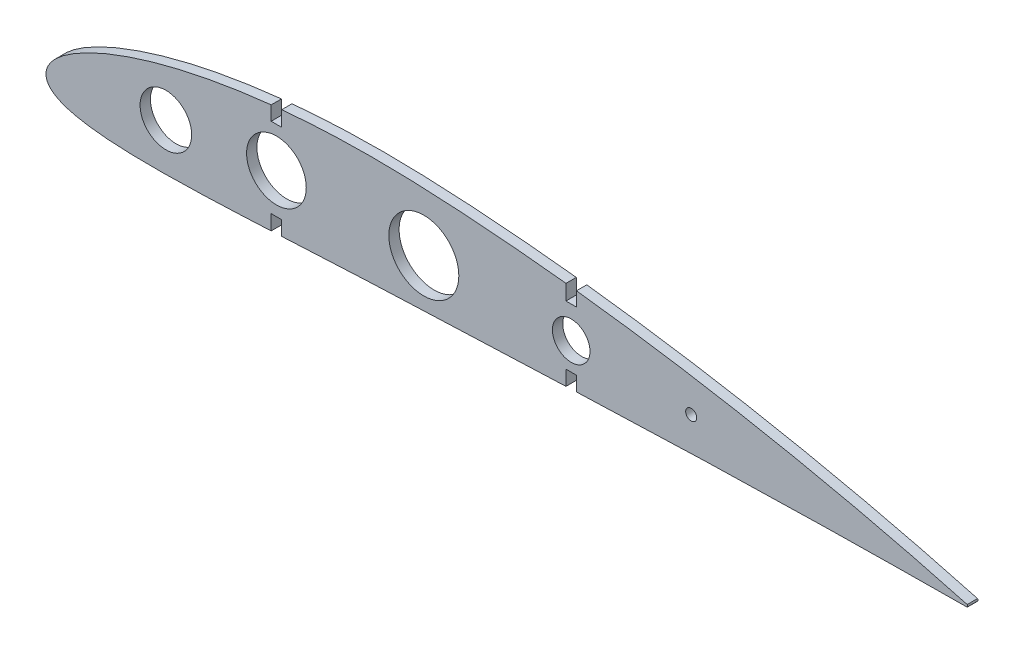
SolidWorks part; units mm, degrees
material "Фанера"
ref_plane "Front Plane" through (0, 0, 0) normal (0, 0, 1) x (1, 0, 0)
ref_plane "Top Plane" through (0, 0, 0) normal (0, 1, 0) x (1, 0, 0)
ref_plane "Right Plane" through (0, 0, 0) normal (1, 0, 0) x (0, 0, -1)
curve "Кривая5"
  spline degree 3 poles (0.048, 0.6214, 0) (0.0227, 0.3735, 0) (-0.0278, -0.1225, 0) (0.078, -0.8844, 0) (0.3497, -1.6388, 0) (0.8143, -2.3651, 0) (1.4635, -3.0393, 0) (2.291, -3.661, 0) (3.3059, -4.2358, 0) (4.5353, -4.7737, 0) (6.0297, -5.2822, 0) (7.869, -5.7653, 0) (10.1688, -6.2217, 0) (13.0754, -6.6396, 0) (16.7281, -6.993, 0) (21.19, -7.2473, 0) (26.4, -7.3766, 0) (32.1974, -7.3763, 0) (38.3978, -7.2614, 0) (44.8576, -7.0566, 0) (51.4865, -6.7865, 0) (58.231, -6.4723, 0) (65.0521, -6.1329, 0) (71.9108, -5.784, 0) (78.7714, -5.4397, 0) (85.6105, -5.111, 0) (92.4321, -4.805, 0) (99.255, -4.532, 0) (106.0974, -4.2783, 0) (112.9692, -4.0031, 0) (119.8644, -3.7232, 0) (126.7739, -3.4401, 0) (133.6816, -3.1587, 0) (140.5819, -2.8824, 0) (147.472, -2.6139, 0) (154.3526, -2.3556, 0) (161.225, -2.1094, 0) (168.0909, -1.8766, 0) (174.9516, -1.6586, 0) (181.8086, -1.4564, 0) (188.6632, -1.2704, 0) (195.5166, -1.1011, 0) (202.3695, -0.9486, 0) (209.2212, -0.8129, 0) (216.0668, -0.6936, 0) (222.8864, -0.5903, 0) (229.6176, -0.5029, 0) (236.0874, -0.4315, 0) (241.9808, -0.3765, 0) (246.559, -0.3395, 0) (249.1205, -0.3213, 0) (250, -0.315, 0) knots 0 0 0 0 0.002941 0.005884 0.009016 0.012365 0.016008 0.020037 0.024574 0.029784 0.035897 0.04324 0.052276 0.063635 0.077983 0.095698 0.11652 0.139661 0.164312 0.189919 0.216157 0.242838 0.269834 0.296993 0.324123 0.351139 0.378036 0.404946 0.431961 0.459078 0.486347 0.513641 0.540929 0.568176 0.59538 0.622543 0.649673 0.676775 0.703855 0.730919 0.757971 0.785018 0.812062 0.839103 0.866132 0.893099 0.919831 0.94581 0.969681 0.98959 1 1 1 1
curve "Кривая6"
  spline degree 3 poles (250, 0.315, 0) (249.1557, 0.545, 0) (246.7202, 1.2085, 0) (242.3913, 2.3583, 0) (236.8498, 3.7876, 0) (230.7799, 5.298, 0) (224.4559, 6.8129, 0) (218.0305, 8.2916, 0) (211.5624, 9.7197, 0) (205.0724, 11.0924, 0) (198.568, 12.4079, 0) (192.0524, 13.6653, 0) (185.5276, 14.8641, 0) (178.9953, 16.0034, 0) (172.4571, 17.0824, 0) (165.9143, 18.0998, 0) (159.3687, 19.0545, 0) (152.8218, 19.9449, 0) (146.2754, 20.7693, 0) (139.7314, 21.5257, 0) (133.1918, 22.212, 0) (126.6587, 22.8257, 0) (120.1368, 23.364, 0) (113.6286, 23.8247, 0) (107.1527, 24.2002, 0) (100.7411, 24.4984, 0) (94.4118, 24.6866, 0) (88.1559, 24.7401, 0) (81.949, 24.6588, 0) (75.7805, 24.441, 0) (69.6537, 24.0819, 0) (63.5754, 23.578, 0) (57.5552, 22.9249, 0) (51.6058, 22.1191, 0) (45.7444, 21.1566, 0) (39.9959, 20.0354, 0) (34.3979, 18.7563, 0) (29.0104, 17.3276, 0) (23.9258, 15.7719, 0) (19.2707, 14.1343, 0) (15.1791, 12.4833, 0) (11.7405, 10.8956, 0) (8.9594, 9.4296, 0) (6.7609, 8.1086, 0) (5.0337, 6.9246, 0) (3.6717, 5.8542, 0) (2.5921, 4.8713, 0) (1.7382, 3.9526, 0) (1.0699, 3.0809, 0) (0.5716, 2.2416, 0) (0.2158, 1.4308, 0) (0.1023, 0.8832, 0) (0.048, 0.6214, 0) knots 0 0 0 0 0.010162 0.029313 0.052012 0.076619 0.101948 0.127526 0.153184 0.178868 0.204558 0.230246 0.255926 0.281594 0.307246 0.332878 0.358485 0.384061 0.409603 0.435104 0.460559 0.485959 0.511303 0.536552 0.561723 0.586629 0.611085 0.635251 0.659272 0.683164 0.706922 0.730536 0.753983 0.777235 0.800246 0.822951 0.845237 0.866916 0.887662 0.906968 0.924203 0.938879 0.950932 0.960693 0.968647 0.975233 0.980795 0.985584 0.989782 0.993521 0.996902 1 1 1 1
sketch "Эскиз1" plane through (0, 0, 0) normal (0, 0, 1) x (1, 0, 0)
  line L0 (250.1305, 0) -> (250.1305, 54.8427) construction
  line L1 (0, 0) -> (0, 70.5199) construction
  line L2 (0, 0) -> (253.0634, 0) construction
  line L3 (62.5326, 62.6361) -> (62.5326, -41.5636) construction
  line L4 (142.5326, 67.9319) -> (142.5326, 25.1988) construction
  line L5 (175.0913, 63.8571) -> (175.0913, -32.3947) construction
  line L6 (32.5326, -14.3434) -> (32.5326, 29.5903) construction
  line L7 (142.5326, 21.1988) -> (142.5326, -57.0034) construction
  line L8 (61.1076, 19.4501) -> (63.9576, 19.4501)
  line L9 (61.1076, 19.4501) -> (61.1076, 23.3031)
  line L11 (63.9576, 19.4501) -> (63.9576, 23.5885)
  line L12 (61.1076, 19.4501) -> (62.5326, 23.4501) construction
  line L13 (62.5326, 23.4501) -> (63.9576, 19.4501) construction
  line L15 (61.1076, -6.3284) -> (61.1076, -2.2577)
  line L16 (61.1076, -2.2577) -> (63.9576, -2.2577)
  line L17 (63.9576, -6.1866) -> (63.9576, -2.2577)
  line L18 (62.5326, -6.2577) -> (63.9576, -2.2577) construction
  line L19 (61.1076, -2.2577) -> (62.5326, -6.2577) construction
  line L20 (141.1076, 17.1988) -> (143.9576, 17.1988)
  line L21 (141.1076, 17.1988) -> (141.1076, 21.3608)
  line L23 (143.9576, 17.1988) -> (143.9576, 21.0336)
  line L24 (141.1076, 17.1988) -> (142.5326, 21.1988) construction
  line L25 (142.5326, 21.1988) -> (143.9576, 17.1988) construction
  line L28 (141.1076, -2.8629) -> (141.1076, 1.1931)
  line L29 (141.1076, 1.1931) -> (143.9576, 1.1931)
  line L30 (143.9576, -2.7512) -> (143.9576, 1.1931)
  line L31 (142.5326, -2.8069) -> (143.9576, 1.1931) construction
  line L32 (141.1076, 1.1931) -> (142.5326, -2.8069) construction
  arc A0 (250, 0.315) -> (250, -0.315) centre (249.685, 0) cw
  circle A1 centre (62.5326, 8.5962) radius 8.1
  circle A2 centre (142.5326, 8.5962) radius 5.1
  circle A3 centre (32.5326, 5.4481) radius 7
  circle A5 centre (102.5326, 8.5962) radius 9.5
  circle A6 centre (175.0913, 7.4939) radius 1.5
  arc A7 (175.0913, 16.6448) -> (175.0913, -1.657) centre (175.0913, 7.4939) ccw
  spline S2 degree 3 poles (0.048, 0.6214) (0.0227, 0.3735) (-0.0278, -0.1225) (0.078, -0.8844) (0.3497, -1.6388) (0.8143, -2.3651) (1.4635, -3.0393) (2.291, -3.661) (3.3059, -4.2358) (4.5353, -4.7737) (6.0297, -5.2822) (7.869, -5.7653) (10.1688, -6.2217) (13.0754, -6.6396) (16.7281, -6.993) (21.19, -7.2473) (26.4, -7.3766) (32.1974, -7.3763) (38.3978, -7.2614) (44.8576, -7.0566) (51.4865, -6.7865) (56.9206, -6.5334) (60.1398, -6.3761) (61.1076, -6.3284) knots 0 0 0 0 0.002941 0.005884 0.009016 0.012365 0.016008 0.020037 0.024574 0.029784 0.035897 0.04324 0.052276 0.063635 0.077983 0.095698 0.11652 0.139661 0.164312 0.189919 0.216157 0.242838 0.254307 0.254307 0.254307 0.254307
  spline S3 degree 3 poles (250, 0.315) (249.1557, 0.545) (246.7202, 1.2085) (242.3913, 2.3583) (236.8498, 3.7876) (230.7799, 5.298) (224.4559, 6.8129) (218.0305, 8.2916) (211.5624, 9.7197) (205.0724, 11.0924) (198.568, 12.4079) (192.0524, 13.6653) (185.5276, 14.8641) (178.9953, 16.0034) (172.4571, 17.0824) (165.9143, 18.0998) (159.3687, 19.0545) (152.8218, 19.9449) (147.6839, 20.5919) (144.7288, 20.9433) (143.9576, 21.0336) knots 0 0 0 0 0.010162 0.029313 0.052012 0.076619 0.101948 0.127526 0.153184 0.178868 0.204558 0.230246 0.255926 0.281594 0.307246 0.332878 0.358485 0.384061 0.409603 0.418619 0.418619 0.418619 0.418619
  spline S4 degree 3 poles (61.1076, 23.3031) (59.9179, 23.1768) (56.7397, 22.8145) (51.6058, 22.1191) (45.7444, 21.1566) (39.9959, 20.0354) (34.3979, 18.7563) (29.0104, 17.3276) (23.9258, 15.7719) (19.2707, 14.1343) (15.1791, 12.4833) (11.7405, 10.8956) (8.9594, 9.4296) (6.7609, 8.1086) (5.0337, 6.9246) (3.6717, 5.8542) (2.5921, 4.8713) (1.7382, 3.9526) (1.0699, 3.0809) (0.5716, 2.2416) (0.2158, 1.4308) (0.1023, 0.8832) (0.048, 0.6214) knots 0.740091 0.740091 0.740091 0.740091 0.753983 0.777235 0.800246 0.822951 0.845237 0.866916 0.887662 0.906968 0.924203 0.938879 0.950932 0.960693 0.968647 0.975233 0.980795 0.985584 0.989782 0.993521 0.996902 1 1 1 1
  spline S5 degree 3 poles (63.9576, -6.1866) (64.3178, -6.1685) (66.9697, -6.0353) (71.9108, -5.784) (78.7714, -5.4397) (85.6105, -5.111) (92.4321, -4.805) (99.255, -4.532) (106.0974, -4.2783) (112.9692, -4.0031) (119.8644, -3.7232) (126.7739, -3.4401) (133.8556, -3.1516) (138.6334, -2.9604) (141.1076, -2.8629) knots 0.265565 0.265565 0.265565 0.265565 0.269834 0.296993 0.324123 0.351139 0.378036 0.404946 0.431961 0.459078 0.486347 0.513641 0.540929 0.570237 0.570237 0.570237 0.570237
  spline S6 degree 3 poles (143.9576, -2.7512) (145.1302, -2.7056) (148.5961, -2.5717) (154.3526, -2.3556) (161.225, -2.1094) (168.0909, -1.8766) (174.9516, -1.6586) (181.8086, -1.4564) (188.6632, -1.2704) (195.5166, -1.1011) (202.3695, -0.9486) (211.4992, -0.7677) (220.6031, -0.6199) (229.6176, -0.5029) (236.0874, -0.4315) (241.9808, -0.3765) (246.559, -0.3395) (249.1205, -0.3213) (250, -0.315) knots 0.58149 0.58149 0.58149 0.58149 0.59538 0.622543 0.649673 0.676775 0.703855 0.730919 0.757971 0.785018 0.812062 0.839103 0.893099 0.919831 0.94581 0.969681 0.98959 1 1 1 1
  spline S7 degree 3 poles (141.1076, 21.3608) (140.6472, 21.4126) (138.0081, 21.7065) (133.1918, 22.212) (126.6587, 22.8257) (120.1368, 23.364) (113.6286, 23.8247) (107.1527, 24.2002) (100.7411, 24.4984) (94.4118, 24.6866) (88.1559, 24.7401) (81.949, 24.6588) (75.7805, 24.441) (69.7854, 24.0896) (65.8508, 23.7665) (63.9576, 23.5885) knots 0.429724 0.429724 0.429724 0.429724 0.435104 0.460559 0.485959 0.511303 0.536552 0.561723 0.586629 0.611085 0.635251 0.659272 0.683164 0.706922 0.729004 0.729004 0.729004 0.729004
  point P22 (62.5326, 23.4501)
  point P23 (62.5326, -6.2577)
  point P26 (32.5326, 18.2506)
  point P27 (32.5326, -7.3543)
  point P30 (62.5326, 23.4501)
  point P31 (62.5326, -6.2577)
  point P40 (142.5326, 21.1988)
  point P43 (142.5326, -2.8069)
  point P53 (175.0913, 16.6448)
  point P56 (175.0913, -1.657)
  point P62 (175.0913, 7.5519)
  dimension "D3" = 16.2
  dimension "D8" = 14
  dimension "D10" = 10.2
  dimension "D9" = 19
  dimension "D27" = 3
  dimension "D1" = 250.1305
  dimension "D2" = 62.5326
  dimension "D4" = 80
  dimension "D5" = 75.0391
  dimension "D6" = 29.7079
  dimension "D7" = 14.8539
  dimension "D11" = 40
  dimension "D12" = 30
  dimension "D13" = 25.6049
  dimension "D14" = 12.8025
  dimension "D15" = 2.85
  dimension "D16" = 4
  dimension "D17" = 1.425
  dimension "D18" = 2.85
  dimension "D19" = 4
  dimension "D20" = 1.425
  dimension "D21" = 2.85
  dimension "D22" = 4
  dimension "D23" = 1.425
  dimension "D24" = 2.85
  dimension "D25" = 4
  dimension "D26" = 1.425
extrude "Бобышка-Вытянуть1" add sketch "Эскиз1" along normal mid plane 2.8 contours L21 S7 L11 L8 L9 S4 S2 L15 L16 L17 S5 L28 L29 L30 S6 A7 S3 L23 L20 A1 A2 A3 A5 | A7 S6 A0 S3 A6
equation "\"D2@Эскиз1\"=\"D1@Эскиз1\"/4"
equation "\"D7@Эскиз1\"=\"D6@Эскиз1\"/2"
equation "\"D5@Эскиз1\"=\"D1@Эскиз1\"*0.3"
equation "\"D14@Эскиз1\"=\"D13@Эскиз1\"/2"
equation "\"t\"= 2.85"
equation "\"D17@Эскиз1\"=\"D15@Эскиз1\"/2"
equation "\"D18@Эскиз1\"=\"t\""
equation "\"D20@Эскиз1\"=\"D18@Эскиз1\"/2"
equation "\"D21@Эскиз1\"=\"t\""
equation "\"D23@Эскиз1\"=\"D21@Эскиз1\"/2"
equation "\"D24@Эскиз1\"=\"t\""
equation "\"D26@Эскиз1\"=\"D24@Эскиз1\"/2"
